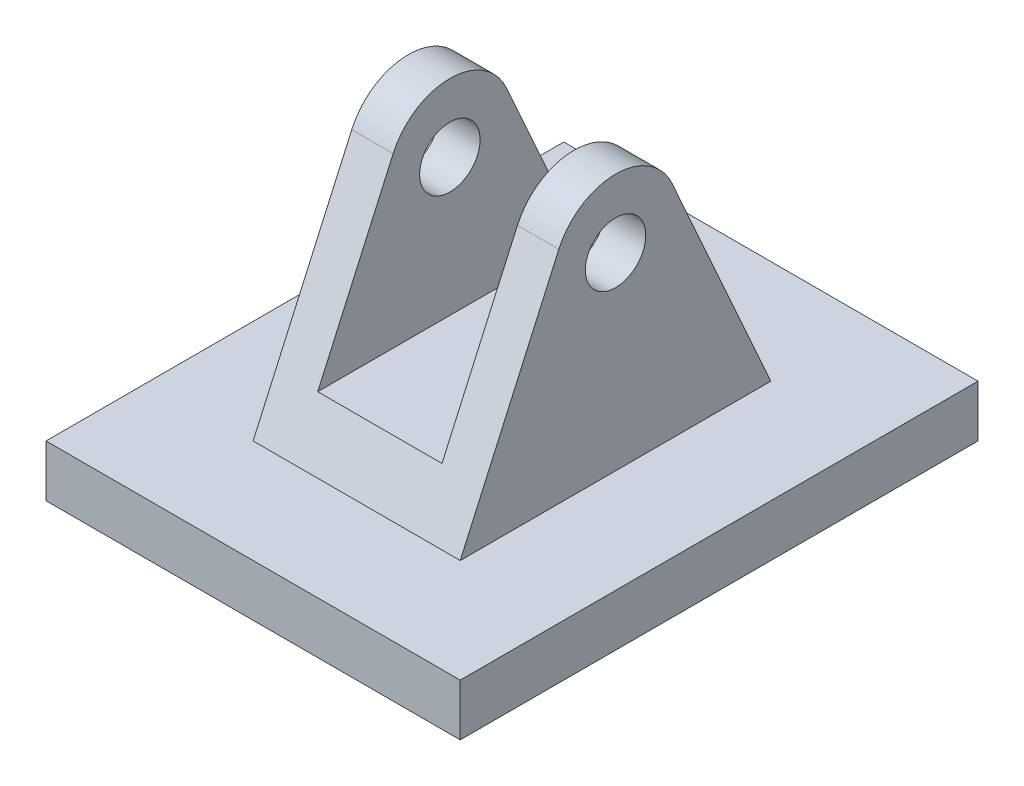
SolidWorks part; units mm, degrees
ref_plane "Front Plane" through (0, 0, 0) normal (0, 0, 1) x (1, 0, 0)
ref_plane "Top Plane" through (0, 0, 0) normal (0, 1, 0) x (1, 0, 0)
ref_plane "Right Plane" through (0, 0, 0) normal (1, 0, 0) x (0, 0, -1)
sketch "Sketch1" plane through (0, 0, 0) normal (0, 1, 0) x (1, 0, 0)
  line L1 (0, 0) -> (80, 0)
  line L2 (0, 0) -> (0, -100)
  line L3 (0, -100) -> (80, -100)
  line L4 (80, 0) -> (80, -100)
  dimension "D1" = 100
  dimension "D2" = 80
extrude "Boss-Extrude1" add sketch "Sketch1" along normal blind 10
sketch "Sketch2" plane through (0, 0, 0) normal (1, 0, 0) x (0, 0, -1)
  line L0 (-80, 10) -> (-20, 10)
  line L1 (-100, 10) -> (0, 10) construction
  line L2 (-20, 10) -> (-50, 77)
  line L3 (-50, 77) -> (-80, 10)
  point P4 (0, 0)
  point P6 (0, 0)
  point P7 (0, 0)
  point P8 (0, 0)
  point P9 (0, 0)
  point P10 (0, 0)
  point P11 (0, 0)
  point P12 (0, 0)
  point P13 (0, 0)
  point P14 (0, 0)
extrude "Boss-Extrude2" add sketch "Sketch2" along normal blind 60 and the other way blind 0.0001 separate body
other "Move Face1" face at (-0.0001, 32.3333, 50) parameters "D1"=20
fillet "Fillet1" radius 12 1 edges at (39.9999, 77, 50)
sketch "Sketch8" plane through (19.9999, 0, 0) normal (-1, 0, 0) x (0, 0, 1)
  circle A0 centre (50, 46.4839) radius 5.841
  point P2 (0, 0)
extrude "Cut-Extrude1" cut sketch "Sketch8" against normal blind 60 contours A0
sketch "Sketch10" plane through (0, 0, 0) normal (0, 0, 1) x (1, 0, 0)
  line L1 (28, 66.5131) -> (52, 66.5131)
  line L2 (28, 66.5131) -> (28, 20)
  line L3 (28, 20) -> (52, 20)
  line L4 (52, 66.5131) -> (52, 20)
extrude "Cut-Extrude2" cut sketch "Sketch10" along normal blind 200 contours L2 L1 L4 L3
